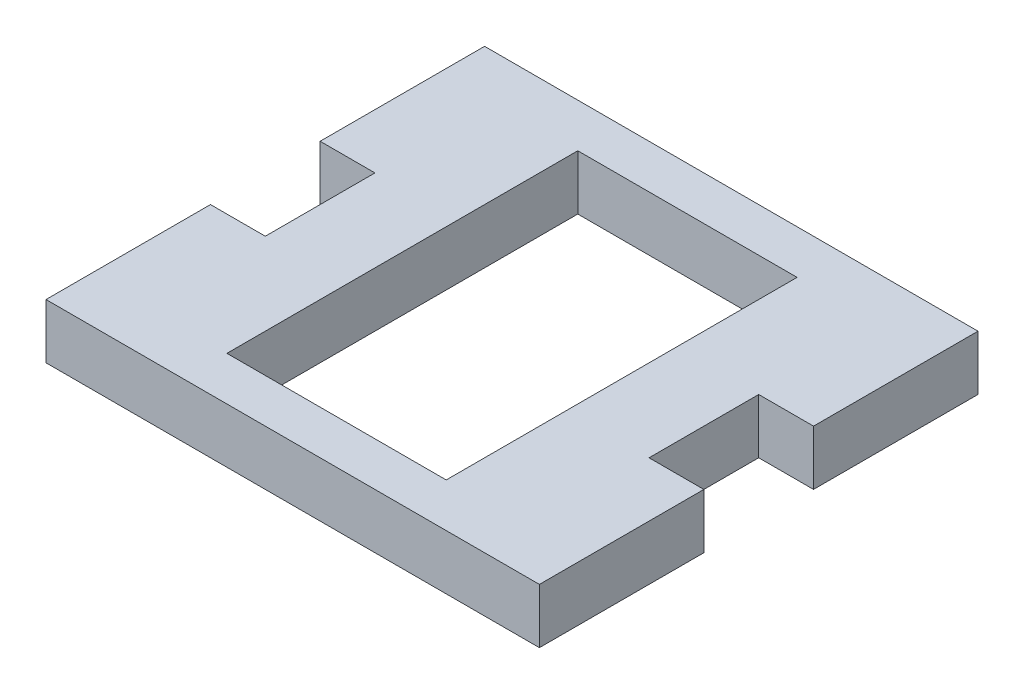
SolidWorks part; units mm, degrees
ref_plane "Front Plane" through (0, 0, 0) normal (0, 0, 1) x (1, 0, 0)
ref_plane "Top Plane" through (0, 0, 0) normal (0, 1, 0) x (1, 0, 0)
ref_plane "Right Plane" through (0, 0, 0) normal (1, 0, 0) x (0, 0, -1)
sketch "Sketch1" plane through (0, 0, 0) normal (0, 1, 0) x (1, 0, 0)
  line L0 (-14.2875, 3.175) -> (-11.1125, 3.175)
  line L1 (-14.2875, -12.7) -> (14.2875, -12.7)
  line L3 (-14.2875, 12.7) -> (14.2875, 12.7)
  line L5 (-14.2875, -12.7) -> (14.2875, 12.7) construction
  line L6 (-14.2875, 12.7) -> (14.2875, -12.7) construction
  line L7 (-6.35, -10.16) -> (6.35, -10.16)
  line L8 (-6.35, -10.16) -> (-6.35, 10.16)
  line L9 (-6.35, 10.16) -> (6.35, 10.16)
  line L10 (6.35, -10.16) -> (6.35, 10.16)
  line L11 (-6.35, -10.16) -> (6.35, 10.16) construction
  line L12 (-6.35, 10.16) -> (6.35, -10.16) construction
  line L13 (-11.1125, 3.175) -> (-11.1125, -3.175)
  line L14 (-11.1125, -3.175) -> (-14.2875, -3.175)
  line L15 (-14.2875, 12.7) -> (-14.2875, 3.175)
  line L16 (-14.2875, -12.7) -> (-14.2875, -3.175)
  line L17 (0, 12.7) -> (0, -12.7) construction
  line L18 (14.2875, -12.7) -> (14.2875, -3.175)
  line L19 (14.2875, 12.7) -> (14.2875, 3.175)
  line L20 (11.1125, -3.175) -> (14.2875, -3.175)
  line L21 (11.1125, 3.175) -> (11.1125, -3.175)
  line L22 (14.2875, 3.175) -> (11.1125, 3.175)
  point P0 (0, 0)
  point P6 (0, 0)
  dimension "D1" = 28.575
  dimension "D2" = 25.4
  dimension "D3" = 2.54
  dimension "D4" = 12.7
  dimension "D5" = 3.175
  dimension "D6" = 6.35
extrude "Boss-Extrude1" add sketch "Sketch1" along normal blind 3.175
